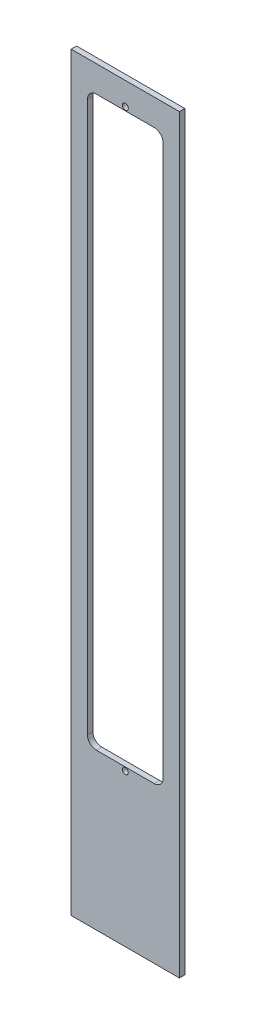
SolidWorks part; units mm, degrees
ref_plane "Plan de face" through (0, 0, 0) normal (0, 0, 1) x (1, 0, 0)
ref_plane "Plan de dessus" through (0, 0, 0) normal (0, 1, 0) x (1, 0, 0)
ref_plane "Plan de droite" through (0, 0, 0) normal (1, 0, 0) x (0, 0, -1)
sketch "Esquisse1" plane through (0, 0, 0) normal (0, 0, 1) x (1, 0, 0)
  line L1 (-60, -416) -> (60, -416)
  line L2 (-60, -416) -> (-60, 416)
  line L3 (-60, 416) -> (60, 416)
  line L4 (60, -416) -> (60, 416)
  line L5 (-60, -416) -> (60, 416) construction
  line L6 (-60, 416) -> (60, -416) construction
  point P0 (0, 0)
  dimension "D1" = 120
  dimension "D2" = 832
extrude "Boss.-Extru.1" add sketch "Esquisse1" along normal blind 6
sketch "Sketch1" plane through (0, 0, 6) normal (0, 0, 1) x (1, 0, 0)
  line L0 (-42, 376.7263) -> (-42, -233.2737)
  line L1 (-32, 386.7263) -> (32, 386.7263)
  line L2 (-32, -243.2737) -> (32, -243.2737)
  line L3 (42, 376.7263) -> (42, -233.2737)
  line L4 (41.9013, -253.2737) -> (-41.9013, -253.2737) construction
  line L5 (-50, -245.175) -> (-50, 388.6276) construction
  line L6 (50, 388.6276) -> (50, -245.175) construction
  line L7 (-41.9013, 396.7263) -> (41.9013, 396.7263) construction
  arc A0 (42, -233.2737) -> (32, -243.2737) centre (32, -233.2737) cw
  arc A1 (-32, 386.7263) -> (-42, 376.7263) centre (-32, 376.7263) ccw
  arc A2 (42, 376.7263) -> (32, 386.7263) centre (32, 376.7263) ccw
  arc A3 (-42, -233.2737) -> (-32, -243.2737) centre (-32, -233.2737) ccw
  dimension "D1" = 10
  dimension "D2" = 8
  dimension "D3" = 8
  dimension "D4" = 10
  dimension "D5" = 10
extrude "Cut-Extrude1" cut sketch "Sketch1" against normal blind 10
hole_wizard "M6 Clearance Hole1" positions "Sketch3" profile "Sketch2" hole size "M6" standard "ANSI Metric"
sketch "Sketch3" plane through (0, 0, 6) normal (0, 0, 1) x (1, 0, 0)
  point P0 (0, 390.7263)
  point P3 (0, -247.2737)
sketch "Sketch2" plane through (0, 390.7263, 6) normal (1, 0, 0) x (0, -1, 0)
  line L0 (0, 0) -> (0, 7.9828)
  line L1 (0, 7.9828) -> (3.3, 6)
  line L2 (3.3, 6) -> (3.3, 0)
  line L5 (3.3, 0) -> (0, 0)
  line L10 (0, 7.9828) -> (-3.3, 6) construction
  line L11 (0, -6.35) -> (0, 107.95) construction
  dimension "Hole Dia." = 6.6
  dimension "Hole Depth" = 6
  dimension "Drill Angle" = 118
